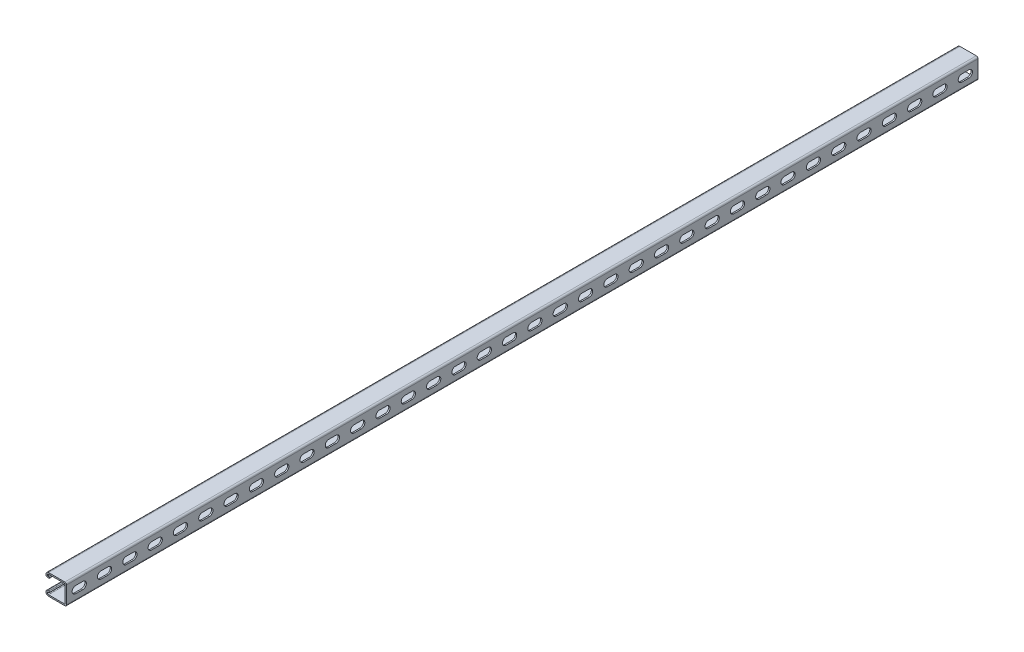
SolidWorks part; units mm, degrees
ref_plane "Front Plane" through (0, 0, 0) normal (0, 0, 1) x (1, 0, 0)
ref_plane "Top Plane" through (0, 0, 0) normal (0, 1, 0) x (1, 0, 0)
ref_plane "Right Plane" through (0, 0, 0) normal (1, 0, 0) x (0, 0, -1)
sketch "Sketch1" plane through (0, 0, 0) normal (0, 0, 1) x (1, 0, 0)
  line L0 (0, 0) -> (-41.275, 0) construction
  line L3 (-41.275, 20.6375) -> (0, 20.6375) construction
  line L4 (-41.275, 20.6375) -> (-41.275, -20.6375) construction
  line L5 (-41.275, -20.6375) -> (0, -20.6375) construction
  line L6 (0, 20.6375) -> (0, -20.6375) construction
  line L7 (-36.2267, 20.6375) -> (-3.4607, 20.6375)
  line L8 (0, 17.1767) -> (0, -17.1767)
  line L9 (-2.794, -17.1767) -> (-2.794, 17.1767)
  line L10 (-3.4608, 17.8435) -> (-36.2267, 17.8435)
  line L11 (-41.275, 15.5892) -> (-41.275, 14.5732)
  line L12 (-37.8142, 11.1125) -> (-35.5346, 11.1125)
  line L14 (-35.5346, 13.9065) -> (-37.8142, 13.9065)
  line L15 (-38.481, 14.5732) -> (-38.481, 15.5892)
  line L16 (-38.481, -14.5733) -> (-38.481, -15.5893)
  line L17 (-35.5346, -13.9065) -> (-37.8142, -13.9065)
  line L18 (-37.8142, -11.1125) -> (-35.5346, -11.1125)
  line L19 (-41.275, -15.5893) -> (-41.275, -14.5733)
  line L20 (-3.4607, -17.8435) -> (-36.2267, -17.8435)
  line L21 (-36.2267, -20.6375) -> (-3.4607, -20.6375)
  line L22 (-2.794, -20.6375) -> (-2.794, 20.6375) construction
  arc A1 (0, 17.1767) -> (-3.4607, 20.6375) centre (-3.4607, 17.1767) ccw
  arc A2 (-2.794, 17.1767) -> (-3.4608, 17.8435) centre (-3.4607, 17.1767) ccw
  arc A4 (-36.2267, 20.6375) -> (-41.275, 15.5892) centre (-36.2267, 15.5892) ccw
  arc A5 (-41.275, 14.5732) -> (-37.8142, 11.1125) centre (-37.8142, 14.5732) ccw
  arc A6 (-35.5346, 11.1125) -> (-35.5346, 13.9065) centre (-35.5346, 12.5095) ccw
  arc A7 (-37.8142, 13.9065) -> (-38.481, 14.5732) centre (-37.8142, 14.5732) cw
  arc A8 (-38.481, 15.5892) -> (-36.2267, 17.8435) centre (-36.2267, 15.5892) cw
  arc A9 (-38.481, -15.5893) -> (-36.2267, -17.8435) centre (-36.2267, -15.5893) ccw
  arc A10 (-37.8142, -13.9065) -> (-38.481, -14.5733) centre (-37.8142, -14.5733) ccw
  arc A11 (-35.5346, -11.1125) -> (-35.5346, -13.9065) centre (-35.5346, -12.5095) cw
  arc A12 (-41.275, -14.5733) -> (-37.8142, -11.1125) centre (-37.8142, -14.5733) cw
  arc A13 (-36.2267, -20.6375) -> (-41.275, -15.5893) centre (-36.2267, -15.5893) cw
  arc A14 (-2.794, -17.1767) -> (-3.4607, -17.8435) centre (-3.4607, -17.1767) cw
  arc A15 (0, -17.1767) -> (-3.4607, -20.6375) centre (-3.4607, -17.1767) cw
  point P24 (0, 20.6375)
  point P65 (-2.794, 0)
  dimension "D1" = 3.4608
  dimension "D2" = 5.0482
  dimension "D3" = 3.4608
  dimension "Ht." = 41.275
  dimension "Wd." = 41.275
  dimension "Thk." = 2.794
  dimension "D4" = 9.525
  dimension "D5" = 7.1374
extrude "Boss-Extrude1" add sketch "Sketch1" against normal blind 1828.8
sketch "Sketch3" plane through (0, 0, 0) normal (1, 0, 0) x (0, 0, -1)
  line L0 (0, 0) -> (1828.8, 0) construction
  point P2 (101.6, 0)
  point P3 (1727.2, 0)
  dimension "D1" = 101.6
  dimension "D2" = 101.6
  dimension "D3" = 1828.8
sketch "Sketch2" plane through (0, 0, 0) normal (1, 0, 0) x (0, 0, -1)
  line L0 (18.2562, 0) -> (32.5437, 0) construction
  line L1 (18.2562, 7.1438) -> (32.5437, 7.1438)
  line L2 (18.2562, -7.1438) -> (32.5437, -7.1438)
  line L3 (18.2562, 0) -> (0, 0) construction
  line L4 (25.4, 0) -> (76.2, 0) construction
  line L5 (0, -17.1767) -> (0, 17.1767) construction
  arc A0 (18.2562, 7.1438) -> (18.2562, -7.1438) centre (18.2562, 0) ccw
  arc A1 (32.5437, -7.1438) -> (32.5437, 7.1438) centre (32.5437, 0) ccw
  point P3 (25.4, 0)
  dimension "Hole to End" = 11.1125
  dimension "D2" = 25.4
extrude "Cut-Extrude1" cut sketch "Sketch2" against normal up to vertex (2.794 mm away) up to point (-2.794, 0, 0)
pattern_linear "LPattern1" count 36 spacing 50.8 along (0, 0, -1) of "Cut-Extrude1"
equation "\"D1@LPattern1\" = \"Slot Ctr.@Sketch2\""
equation "\"Hole Count@LPattern1\" = \"Lg.@Boss-Extrude1\" / \"D1@LPattern1\""
equation "\"D3@Sketch3\" = \"Lg.@Boss-Extrude1\""
